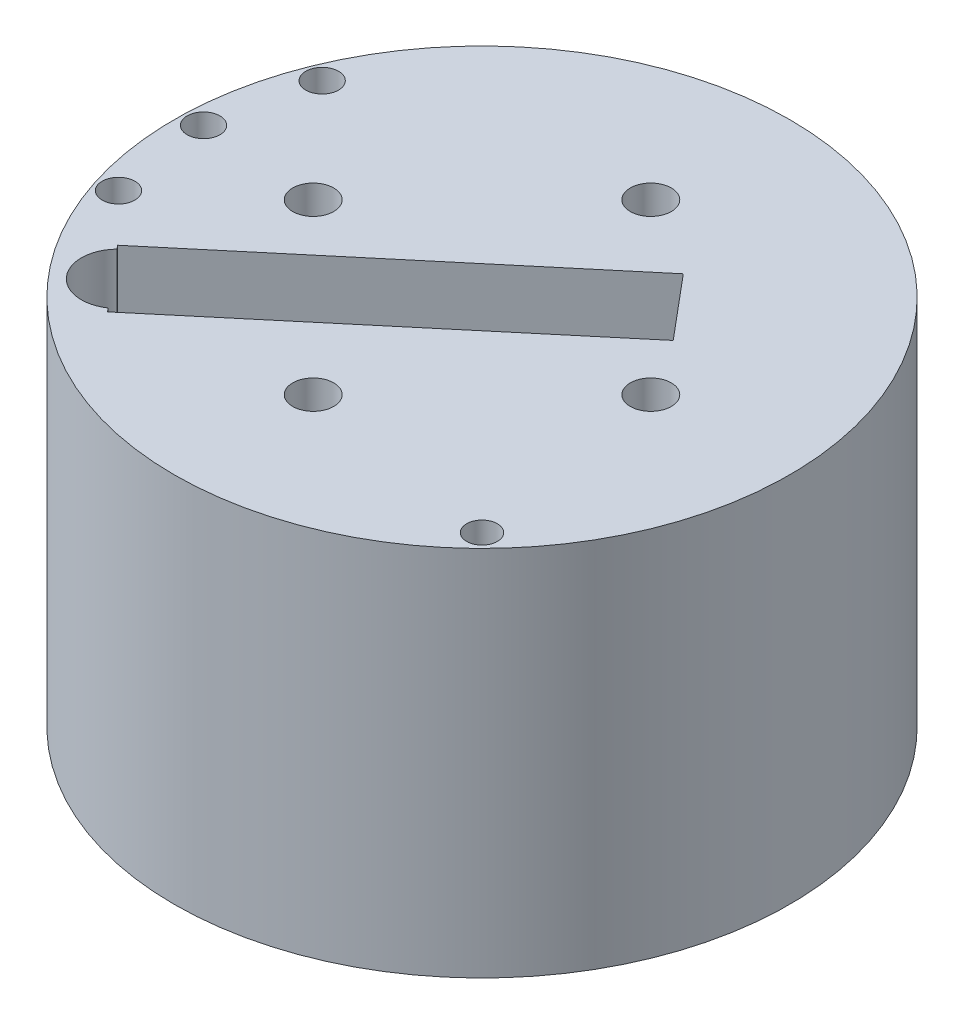
SolidWorks part; units mm, degrees
ref_plane "Front Plane" through (0, 0, 0) normal (0, 0, 1) x (1, 0, 0)
ref_plane "Top Plane" through (0, 0, 0) normal (0, 1, 0) x (1, 0, 0)
ref_plane "Right Plane" through (0, 0, 0) normal (1, 0, 0) x (0, 0, -1)
sketch "Sketch2" plane through (0, 0, 0) normal (0, 1, 0) x (1, 0, 0)
  circle A0 centre (0, 0) radius 47.6885
  dimension "D1" = 95.377
extrude "Boss-Extrude1" add sketch "Sketch2" along normal blind 57.658
sketch "Sketch4" plane through (0, 57.658, 0) normal (0, 1, 0) x (1, 0, 0)
  circle A1 centre (-26.162, 0) radius 3.175
  circle A2 centre (26.162, 0) radius 3.175
  circle A3 centre (0, 26.162) radius 3.175
  circle A4 centre (0, -26.162) radius 3.175
sketch "Sketch5" plane through (0, 57.658, 0) normal (0, 1, 0) x (1, 0, 0)
  line L0 (0, 0) -> (-44.6487, 1.4926)
  line L1 (0, 0) -> (-41.4455, 16.6734)
  line L2 (0, 0) -> (-42.4665, -13.8681)
  line L4 (0, 0) -> (-30.6943, -25.7555)
  circle A1 centre (-41.4455, 16.6734) radius 2.54
  circle A2 centre (0, 0) radius 44.6736
  circle A3 centre (-44.6487, 1.4926) radius 2.54
  circle A4 centre (-42.4665, -13.8681) radius 2.54
  circle A9 centre (-30.6943, -25.7555) radius 5.6388
  dimension "D3" = 11.2776
  dimension "D5" = 89.3472
  dimension "D1" = 20
  dimension "D2" = 20
  dimension "D6" = 21.915
  dimension "D4" = 40.0685
extrude "Cut-Extrude2" cut sketch "Sketch5" against normal through all contours A9 | A1 | A3 | A4
extrude "Cut-Extrude3" cut sketch "Sketch4" against normal through all
sketch "Sketch6" plane through (0, 57.658, 0) normal (0, 1, 0) x (1, 0, 0)
  line L1 (-27.0503, -30.9873) -> (20.6206, 9.0134)
  line L2 (-27.0503, -30.9873) -> (-35.2137, -21.2585)
  line L3 (-35.2137, -21.2585) -> (12.4572, 18.7422)
  line L4 (20.6206, 9.0134) -> (12.4572, 18.7422)
  dimension "D1" = 62.23
  dimension "D2" = 12.7
  dimension "D3" = 6.35
  dimension "D4" = 21.59
  dimension "D5" = 90
  dimension "D6" = 90
  dimension "D7" = 90
extrude "Cut-Extrude4" cut sketch "Sketch6" against normal blind 43.18
sketch "Sketch11" plane through (0, 0, 0) normal (0, -1, 0) x (1, 0, 0)
  circle A0 centre (0, 26.162) radius 6.35
  circle A1 centre (26.162, 0) radius 6.35
  circle A2 centre (0, -26.162) radius 6.35
  circle A3 centre (-26.162, 0) radius 6.35
  dimension "D1" = 12.7
  dimension "D2" = 12.7
  dimension "D3" = 12.7
  dimension "D4" = 12.7
extrude "Cut-Extrude7" cut sketch "Sketch11" against normal blind 7.62
sketch "Sketch14" plane through (0, 0, 0) normal (0, -1, 0) x (1, 0, 0)
  circle A0 centre (1.3569, -14.949) radius 2.067
  circle A1 centre (4.5237, 8.9723) radius 2.067
extrude "Cut-Extrude8" cut sketch "Sketch14" against normal blind 19.05
sketch "Sketch15" plane through (0, 0, 0) normal (0, -1, 0) x (1, 0, 0)
  line L0 (47.6885, 0) -> (-47.6885, 0)
  line L1 (0, -47.6885) -> (0, 47.6885)
  line L2 (-30.6943, 25.7555) -> (0, 0)
  line L3 (0, 0) -> (-44.6487, -1.4926) construction
  line L4 (0, 0) -> (-41.4455, -16.6734) construction
  line L5 (0, 0) -> (31.589, 31.589)
  circle A0 centre (0, 0) radius 47.6885 construction
  circle A1 centre (1.3569, -14.949) radius 2.067 construction
  circle A2 centre (1.3569, -14.949) radius 2.067 construction
  circle A3 centre (4.5237, 8.9723) radius 2.067 construction
  circle A4 centre (31.589, 31.589) radius 2.3812
  point P9 (0, 0)
  dimension "D1" = 1.3569
  dimension "D2" = 14.949
  dimension "D3" = 8.9723
  dimension "D4" = 4.5237
  dimension "D6" = 40
  dimension "D7" = 44.6736
  dimension "D5" = 40.0685
extrude "Cut-Extrude9" cut sketch "Sketch15" against normal blind 66.04 contours A4
equation "\"D4@Sketch5\"=(3.755/2)-(0.5/2)-0.05"
equation "\"D1@Sketch6\"=2.10 + (0.85-0.5)"
